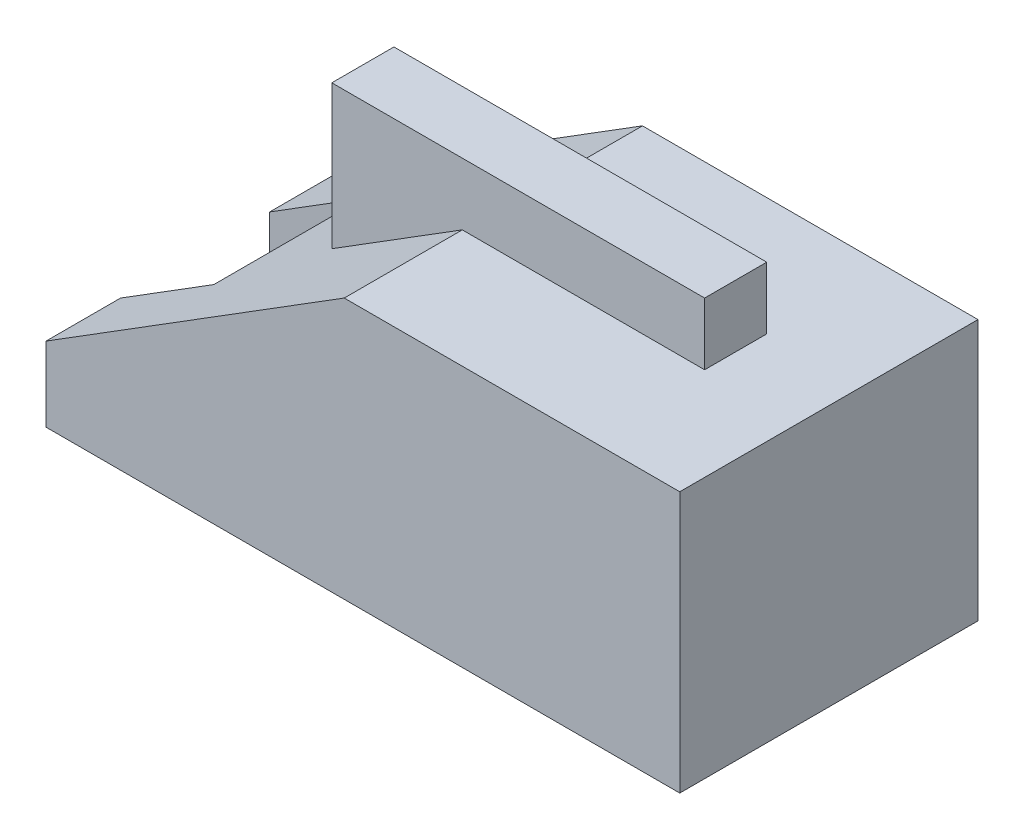
SolidWorks part; units mm, degrees
ref_plane "Front Plane" through (0, 0, 0) normal (0, 0, 1) x (1, 0, 0)
ref_plane "Top Plane" through (0, 0, 0) normal (0, 1, 0) x (1, 0, 0)
ref_plane "Right Plane" through (0, 0, 0) normal (1, 0, 0) x (0, 0, -1)
sketch "Sketch1" plane through (0, 0, 0) normal (0, 0, 1) x (1, 0, 0)
  line L0 (0, 0) -> (102, 0)
  line L1 (102, 0) -> (102, 42)
  line L2 (102, 42) -> (48, 42)
  line L3 (48, 42) -> (0, 12)
  line L4 (0, 12) -> (0, 0)
  dimension "D1" = 102
  dimension "D2" = 54
  dimension "D3" = 42
  dimension "D4" = 12
extrude "Boss-Extrude1" add sketch "Sketch1" along normal mid plane 48
sketch "Sketch2" plane through (0, 0, 0) normal (0, 1, 0) x (1, 0, 0)
  line L0 (0, 0) -> (102, 0) construction
  line L1 (102, -24) -> (102, 24) construction
  line L3 (27, -5) -> (87, -5)
  line L4 (27, -5) -> (27, 5)
  line L5 (27, 5) -> (87, 5)
  line L6 (87, -5) -> (87, 5)
  line L7 (27, -5) -> (87, 5) construction
  line L8 (27, 5) -> (87, -5) construction
  point P5 (57, 0)
  point P10 (0, 0)
  point P11 (0, 0)
  dimension "D1" = 10
  dimension "D2" = 15
  dimension "D3" = 60
extrude "Boss-Extrude2" add sketch "Sketch2" along normal blind 52
sketch "Sketch3" plane through (0, 0, 0) normal (0, 1, 0) x (1, 0, 0)
  line L1 (0, -12) -> (15, -12)
  line L2 (0, -12) -> (0, 12)
  line L3 (0, 12) -> (15, 12)
  line L4 (15, -12) -> (15, 12)
  line L5 (0, -12) -> (15, 12) construction
  line L6 (0, 12) -> (15, -12) construction
  point P0 (7.5, 0)
  dimension "D1" = 15
  dimension "D2" = 24
extrude "Cut-Extrude1" cut sketch "Sketch3" along normal up to next
